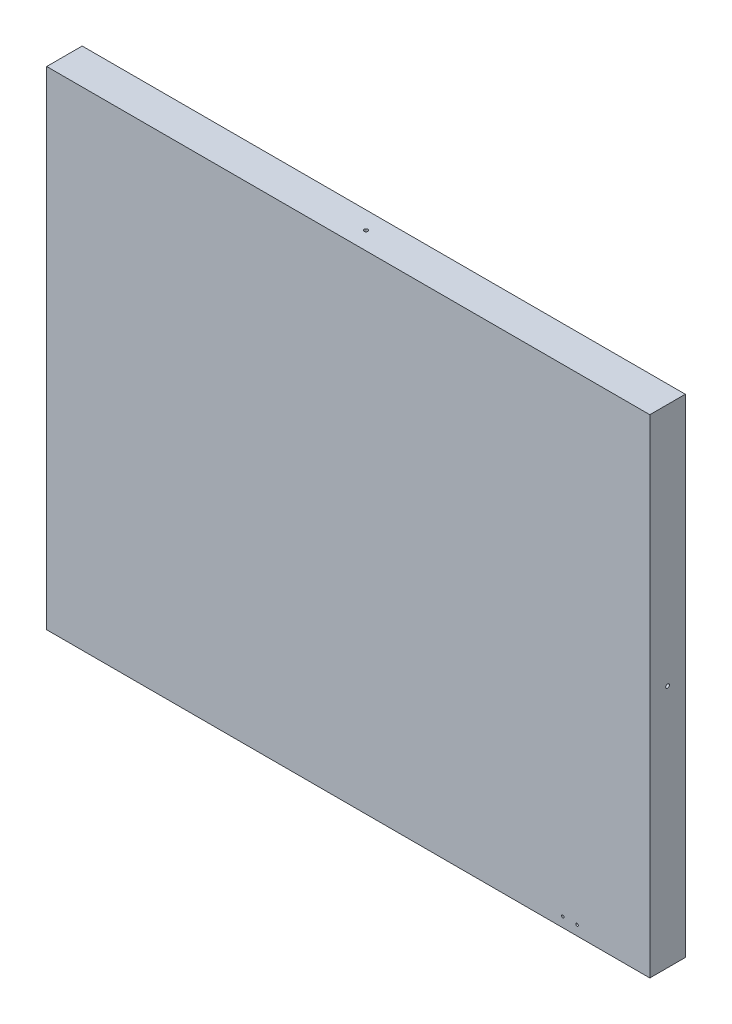
SolidWorks part; units mm, degrees
material "1.4511 (X3CrNb17)"
ref_plane "前视基准面" through (0, 0, 0) normal (0, 0, 1) x (1, 0, 0)
ref_plane "上视基准面" through (0, 0, 0) normal (0, 1, 0) x (1, 0, 0)
ref_plane "右视基准面" through (0, 0, 0) normal (1, 0, 0) x (0, 0, -1)
sketch "草图1" plane through (0, 0, 0) normal (0, 0, 1) x (1, 0, 0)
  line L1 (-340, 275) -> (340, 275)
  line L2 (-340, 275) -> (-340, -275)
  line L3 (-340, -275) -> (340, -275)
  line L4 (340, 275) -> (340, -275)
  line L5 (-340, 275) -> (340, -275) construction
  line L6 (-340, -275) -> (340, 275) construction
  point P0 (0, 0)
  dimension "D1" = 680
  dimension "D2" = 550
extrude "凸台-拉伸1" add sketch "草图1" along normal blind 40
sketch "草图2" plane through (0, -275, 0) normal (0, -1, 0) x (1, 0, 0)
  line L0 (-340, 40) -> (-340, 0) construction
  point P0 (0, 20)
  dimension "D1" = 340
hole_wizard "M5 螺纹孔1" positions "草图3" profile "草图4" tap size "M5" standard "GB" end condition through all
sketch "草图3" plane through (0, -275, 0) normal (0, -1, 0) x (-1, 0, 0)
  point P0 (0, -20)
sketch "草图4" plane through (0, -275, 20) normal (1, 0, 0) x (0, 0, -1)
  line L0 (0, 0) -> (0, 550)
  line L1 (0, 550) -> (2.1, 550)
  line L2 (2.1, 550) -> (2.1, 0)
  line L5 (2.1, 0) -> (0, 0)
  line L11 (0, -6.35) -> (0, 107.95) construction
  dimension "通孔螺纹孔钻头直径" = 4.2
  dimension "通孔螺纹孔钻头深度" = 550
cosmetic thread "孔螺蚊线1" parameters "D2"=5
sketch "草图5" plane through (-340, 0, 0) normal (-1, 0, 0) x (0, 0, 1)
  line L0 (40, 275) -> (0, 275) construction
  point P0 (20, 0)
  dimension "D1" = 275
hole_wizard "M5 螺纹孔2" positions "草图6" profile "草图7" tap size "M5" standard "GB" end condition through all
sketch "草图6" plane through (-340, 0, 0) normal (-1, 0, 0) x (0, 0, 1)
  point P0 (20, 0)
sketch "草图7" plane through (-340, 0, 20) normal (0, 1, 0) x (0, 0, 1)
  line L0 (0, 0) -> (0, 680)
  line L1 (0, 680) -> (2.1, 680)
  line L2 (2.1, 680) -> (2.1, 0)
  line L5 (2.1, 0) -> (0, 0)
  line L11 (0, -6.35) -> (0, 107.95) construction
  dimension "通孔螺纹孔钻头直径" = 4.2
  dimension "通孔螺纹孔钻头深度" = 680
cosmetic thread "孔螺蚊线2" parameters "D2"=5
sketch "草图8" plane through (0, 0, 40) normal (0, 0, 1) x (1, 0, 0)
  line L0 (242, -264) -> (258, -264) construction
  line L1 (-340, -275) -> (340, -275) construction
  line L2 (340, -275) -> (340, 275) construction
  dimension "D1" = 16
  dimension "D2" = 11
  dimension "D3" = 82
hole_wizard "M3.5 螺纹孔1" positions "草图9" profile "草图10" tap size "M3.5" standard "GB"
sketch "草图9" plane through (0, 0, 40) normal (0, 0, 1) x (1, 0, 0)
  point P0 (258, -264)
  point P3 (242, -264)
cosmetic thread "孔螺蚊线3" parameters "D1"=40, "D2"=3.5
cosmetic thread "孔螺蚊线4" parameters "D1"=40, "D2"=3.5
sketch "草图10" plane through (258, -264, 40) normal (1, 0, 0) x (0, -1, 0)
  line L0 (0, 0) -> (0, 5.8712)
  line L1 (0, 5.8712) -> (1.45, 5)
  line L2 (1.45, 5) -> (1.45, 0)
  line L5 (1.45, 0) -> (0, 0)
  line L10 (0, 5.8712) -> (-1.45, 5) construction
  line L11 (0, -6.35) -> (0, 107.95) construction
  dimension "螺纹孔钻头直径" = 2.9
  dimension "螺纹孔钻头深度" = 5
  dimension "导头角度" = 118
